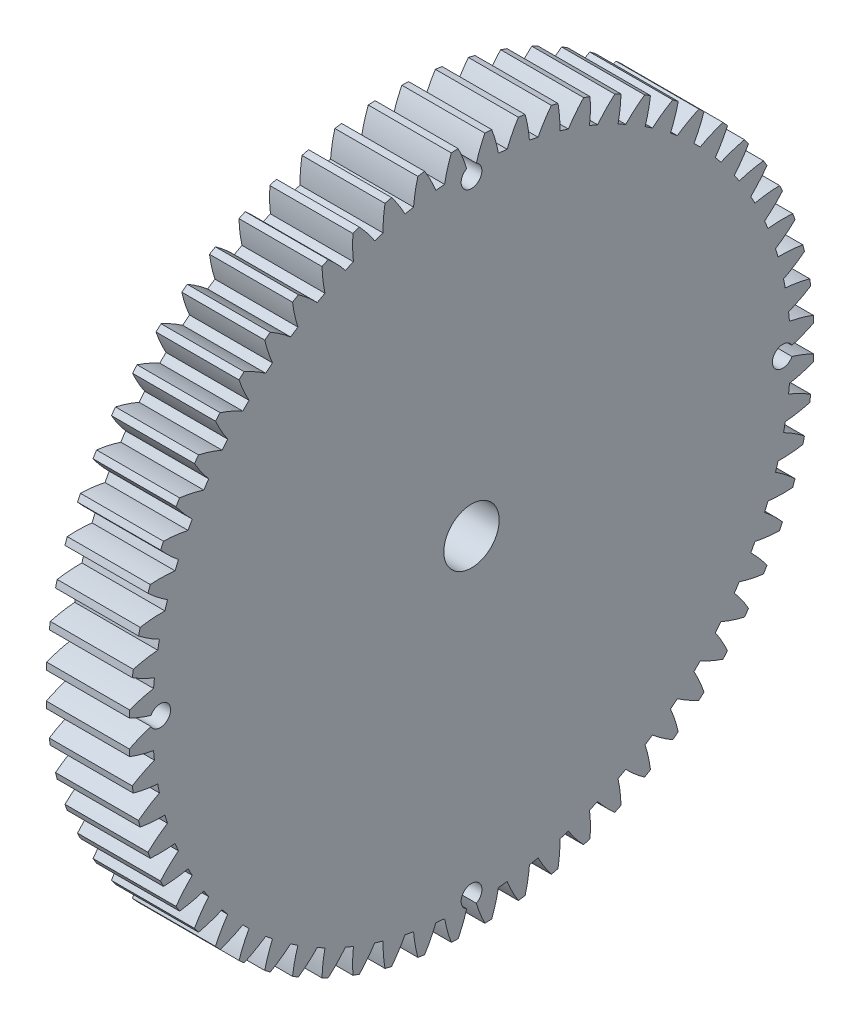
SolidWorks part; units mm, degrees
ref_plane "Plane1" through (0, 0, 0) normal (0, 0, 1) x (1, 0, 0)
ref_plane "Plane2" through (0, 0, 0) normal (0, 1, 0) x (1, 0, 0)
ref_plane "Plane3" through (0, 0, 0) normal (1, 0, 0) x (0, 0, -1)
sketch "HoldingSke" plane through (0, 0, 0) normal (0, 1, 0) x (1, 0, 0)
  line L0 (0, 0) -> (0.2922, -0.5992)
  line L1 (-15, 0) -> (100, 0) construction
  line L2 (0, 0) -> (-2.1039, 2.3779)
  line L3 (0, 0) -> (-11.863, 4.5341)
  line L4 (0, 0) -> (3.7858, 7.762)
  line L5 (0, 0) -> (-46.8476, -17.4728)
  line L6 (0, 0) -> (-9.9476, -6.7116)
  line L7 (-2.1039, 2.3779) -> (8.6586, 51.2059)
  line L8 (-76.2, 54.61) -> (-74.8, 54.61)
  line L9 (-71.009, 38.7566) -> (-53.1078, 45.2721)
  line L10 (-76.2, 71.12) -> (104.1128, 71.12)
  line L11 (0, 0) -> (-12, 0)
  line L12 (-76.2, 101.6) -> (-76.147, 101.6)
  line L13 (24.9733, 27.94) -> (52.9518, 28.4284)
  line L14 (24.9733, 27.94) -> (24.9743, 27.94)
  line L15 (24.9733, 27.94) -> (100.4006, 29.5858)
  line L16 (-63.627, -1.5) -> (-12.827, -1.5)
  circle A0 centre (0, 0) radius 4
  circle A1 centre (0, 0) radius 37.5
  circle A2 centre (0, 0) radius 37.5
  circle A3 centre (0, 0) radius 4
  dimension "MHD" = 75
  dimension "Hub_dia" = 75
  dimension "Bore" = 8
  dimension "MBD" = 8
  dimension "Num_teeth" = 64
  dimension "Pitch" = 0.6667
  dimension "Overall_len" = 50
  dimension "Show_teeth" = 64
  dimension "Thickness" = 12
  dimension "OAL" = 50.0001
  dimension "T_dim" = 1.4
  dimension "Ap" = 20
  dimension "H" = 19.05
  dimension "Pitch_radius" = 180.3128
  dimension "Width" = 12
  dimension "Backlash" = 0.053
  dimension "Addendum_fac" = 1
  dimension "Dedendum_fac" = 1.25
  dimension "Clearance_fac" = 0.25
  dimension "Dedendum_add" = 0.001
  dimension "Module" = 1.5
sketch "BasProSke" plane through (0, 0, 0) normal (0, 1, 0) x (1, 0, 0)
  line L0 (-10, 0) -> (60, 0) construction
  line L1 (0, 0) -> (0, 49.5)
  line L2 (0, 0) -> (12, 0)
  line L3 (12, 0) -> (12, 49.5)
  line L4 (12, 49.5) -> (0, 49.5)
  dimension "Thickness" = 12
  dimension "Diameter" = 99
revolve "Base-Revolve" add sketch "BasProSke" angle 360 about L0
sketch "TooCutSke" plane through (0, 0, 0) normal (1, 0, 0) x (0, 0, -1)
  line L1 (0, 0) -> (0, 107) construction
  line L2 (0, 0) -> (-1.2707, 47.9832) construction
  line L3 (0, 0) -> (-4.7093, 95.8599) construction
  line L4 (-1.2707, 47.9832) -> (-2.3546, 47.9299) construction
  arc A0 (0.6351, 46.1196) -> (-0.6351, 46.1196) centre (0, 0) ccw
  arc A1 (1.9477, 49.4871) -> (-1.9477, 49.4871) centre (0, 0) ccw
  circle A2 centre (0, 0) radius 48 construction
  circle A3 centre (0, 0) radius 45.1052 construction
  arc A4 (-0.6351, 46.1196) -> (-1.9477, 49.4871) centre (-19.101, 40.8612) ccw
  arc A5 (1.9477, 49.4871) -> (0.6351, 46.1196) centre (19.101, 40.8612) ccw
  dimension "Root_dia" = 92.248
  dimension "Overcut_dia" = 99.0508
  dimension "Pitch_dia" = 96
  dimension "Base_dia" = 90.2105
  dimension "Flank_rad" = 19.2
  dimension "Half_ang" = 2.813
  dimension "Half_CT" = 1.0852
extrude "ToothCut" cut sketch "TooCutSke" along normal through all
fillet "Breaks" [suppressed] radius 0.03
fillet "RootFillets" [suppressed] radius 0.376
pattern_circular "TeethCuts" count 64 every 5.625 about axis through (-10, 0, 0) along (1, 0, 0) of "ToothCut", "RootFillets", "Breaks"
sketch "HubNeaOneSke" plane through (0, 0, 0) normal (-1, 0, 0) x (0, 0, 1)
  circle A0 centre (0, 0) radius 37.5
  dimension "Diameter" = 75
extrude "HubNearOne" [suppressed] add sketch "HubNeaOneSke" along normal blind 38.0001
sketch "HubNeaBotSke" plane through (0, 0, 0) normal (-1, 0, 0) x (0, 0, 1)
  circle A0 centre (0, 0) radius 37.5
  dimension "Diameter" = 75
extrude "HubNearBoth" [suppressed] add sketch "HubNeaBotSke" along normal blind 19
ref_plane "FarPln" through (12, 0, 0) normal (1, 0, 0) x (0, 0, -1)
sketch "HubFarSke" plane through (12, 0, 0) normal (1, 0, 0) x (0, 0, -1)
  circle A0 centre (0, 0) radius 37.5
  dimension "Diameter" = 75
extrude "HubFar" [suppressed] add sketch "HubFarSke" along normal blind 19
sketch "BorSke" plane through (0, 0, 0) normal (1, 0, 0) x (0, 0, -1)
  circle A0 centre (0, 0) radius 4
  dimension "Diameter" = 8
extrude "Bore" cut sketch "BorSke" along normal mid plane 100.0001
sketch "KeySke" plane through (0, 0, 0) normal (1, 0, 0) x (0, 0, -1)
  line L0 (-1.5, 0) -> (-1.5, 5.4)
  line L1 (-1.5, 5.4) -> (1.5, 5.4)
  line L2 (1.5, 5.4) -> (1.5, 0)
  line L3 (0, 0) -> (0, 34) construction
  line L4 (-1.5, 0) -> (1.5, 0)
  dimension "Offset" = 5.4
  dimension "Width" = 3
extrude "Keyway" [suppressed] cut sketch "KeySke" along normal mid plane 100.0001
pattern_circular "Keyway2" [suppressed] count 2 every 90 about axis through (-10, 0, 0) along (1, 0, 0)
sketch "Sketch3" plane through (12, 0, 0) normal (1, 0, 0) x (0, 0, -1)
  line L0 (0, 0) -> (0, 45) construction
  line L1 (0, 43.7615) -> (0, 0) construction
  line L2 (0, 0) -> (70.0912, 0) construction
  line L3 (-45, 0) -> (0, 0) construction
  line L5 (0, -45) -> (0, 0) construction
  line L6 (45, 0) -> (0, 0) construction
  circle A0 centre (0, 45) radius 1.5
  circle A1 centre (45, 0) radius 1.5
  circle A2 centre (0, -45) radius 1.5
  circle A3 centre (-45, 0) radius 1.5
  dimension "D2" = 3
  dimension "D1" = 45
extrude "Cut-Extrude1" cut sketch "Sketch3" against normal through all
equation "' \"Module@HoldingSke\" = 6.35"
equation "' \"Num_teeth@HoldingSke\" = 12"
equation "' \"Ap@HoldingSke\" =  20"
equation "' \"Ap@HoldingSke\" = 20"
equation "' \"Width@HoldingSke\" = 0.5 * 25.4"
equation "' \"Hub_dia@HoldingSke\"= 1 * 25.4"
equation "' \"Hub_dia@HoldingSke\" = 1 * 25.4"
equation "' \"Overall_len@HoldingSke\" = 1.0 * 25.4"
equation "' \"Bore@HoldingSke\" = 0.75 * 25.4"
equation "' \"T_dim@HoldingSke\" = 0.1 * 25.4"
equation "' \"Width@KeySke\" = 0.25 * 25.4"
equation "' \"Show_teeth@HoldingSke\" = 13"
equation "' \"Backlash@HoldingSke\" = 0.009 * 25.4"
equation "' \"Addendum_fac@HoldingSke\" = 1.0"
equation "' \"Dedendum_fac@HoldingSke\" = 1.25"
equation "' \"Dedendum_add@HoldingSke\" = 0.00005 * 25.4"
equation "' \"Clearance_fac@HoldingSke\" = 0.25"
equation "\"Pitch@HoldingSke\" = 1 / \"Module@HoldingSke\""
equation "\"Overcut_dia@TooCutSke\" = (\"Num_teeth@HoldingSke\" + 2 * \"Addendum_fac@HoldingSke\") / \"Pitch@HoldingSke\" + 0.002 * 25.4"
equation "\"Pitch_dia@TooCutSke\" = \"Num_teeth@HoldingSke\" / \"Pitch@HoldingSke\""
equation "\"Base_dia@TooCutSke\" = \"Num_teeth@HoldingSke\" / \"Pitch@HoldingSke\" * cos((\"Ap@HoldingSke\"  * 3.14159265 / 180))"
equation "\"Root_dia@TooCutSke\" = (\"Num_teeth@HoldingSke\" + 2) / \"Pitch@HoldingSke\" - 2 * (\"Addendum_fac@HoldingSke\" + \"Dedendum_fac@HoldingSke\") / \"Pitch@HoldingSke\" - \"Dedendum_add@HoldingSke\" * 2"
equation "\"Half_ang@TooCutSke\" = 180 / \"Num_teeth@HoldingSke\""
equation "\"Half_CT@TooCutSke\" = \"Num_teeth@HoldingSke\" / \"Pitch@HoldingSke\" * sin((3.14159265 / 2 / \"Num_teeth@HoldingSke\")) / 2 - 7 * \"Backlash@HoldingSke\" / 4"
equation "\"Flank_rad@TooCutSke\" = \"Num_teeth@HoldingSke\" / \"Pitch@HoldingSke\" / 5"
equation "\"Radius@RootFillets\" = \"Clearance_fac@HoldingSke\" / \"Pitch@HoldingSke\" + \"Dedendum_add@HoldingSke\""
equation "\"Break_rad@Breaks\" = 0.02 / \"Pitch@HoldingSke\""
equation "\"Thickness@HoldingSke\" = \"Width@HoldingSke\""
equation "\"OAL@HoldingSke\" = \"Thickness@HoldingSke\""
equation "\"MHD@HoldingSke\" = (\"Num_teeth@HoldingSke\" + 2) / \"Pitch@HoldingSke\" - 2 * (\"Addendum_fac@HoldingSke\" + \"Dedendum_fac@HoldingSke\")  / \"Pitch@HoldingSke\" - \"Dedendum_add@HoldingSke\" * 2"
equation "\"MBD@HoldingSke\" = (\"Num_teeth@HoldingSke\" + 2) / \"Pitch@HoldingSke\" - 2 * (\"Addendum_fac@HoldingSke\" + \"Dedendum_fac@HoldingSke\")  / \"Pitch@HoldingSke\" - \"Dedendum_add@HoldingSke\" * 2 - 0.002 * 25.4"
equation "\"MHD@HoldingSke\" = ((sgn( \"MHD@HoldingSke\" - \"Hub_dia@HoldingSke\" )-1)*( \"MHD@HoldingSke\" - \"Hub_dia@HoldingSke\" ))/-2+ \"Hub_dia@HoldingSke\""
equation "\"MBD@HoldingSke\" = ((sgn( \"MBD@HoldingSke\" - \"Bore@HoldingSke\" )-1)*( \"MBD@HoldingSke\" - \"Bore@HoldingSke\" ))/-2+ \"Bore@HoldingSke\""
equation "\"OAL@HoldingSke\" = ((sgn( \"OAL@HoldingSke\" - \"Overall_len@HoldingSke\" )+1)*( \"OAL@HoldingSke\" - \"Overall_len@HoldingSke\" ))/2 + \"Overall_len@HoldingSke\" + 0.000002 * 25.4"
equation "\"Num_teeth@TeethCuts\" = int( \"Show_teeth@HoldingSke\" ) + 1"
equation "\"Num_teeth@TeethCuts\" = ((sgn( \"Num_teeth@TeethCuts\" - \"Num_teeth@HoldingSke\" )-1)*( \"Num_teeth@TeethCuts\" - \"Num_teeth@HoldingSke\" ))/-2+ \"Num_teeth@HoldingSke\""
equation "\"Num_teeth@TeethCuts\" = ((sgn( \"Num_teeth@TeethCuts\" - 2.0)+1)*( \"Num_teeth@TeethCuts\" - 2.0))/2 +2.0"
equation "\"Angle@TeethCuts\" = 360.0 / \"Num_teeth@HoldingSke\""
equation "\"Diameter@BasProSke\" = (\"Num_teeth@HoldingSke\" + 2 * \"Addendum_fac@HoldingSke\") / \"Pitch@HoldingSke\""
equation "\"Thickness@BasProSke\"  = \"Thickness@HoldingSke\""
equation "' \"Fillet_rad@BasProSke\" =  \"Thickness@HoldingSke\" * 0.05"
equation "' \"Fillet_rad@BasProSke\" = \"Thickness@HoldingSke\" * 0.05"
equation "\"MHD@HoldingSke\" = ((sgn( \"MHD@HoldingSke\" - \"Root_dia@TooCutSke\" )-1)*( \"MHD@HoldingSke\" - \"Root_dia@TooCutSke\" ))/-2+ \"Root_dia@TooCutSke\""
equation "\"Diameter@HubNeaOneSke\" = \"MHD@HoldingSke\""
equation "\"Length@HubNearOne\" = \"OAL@HoldingSke\" - \"Thickness@BasProSke\""
equation "\"Diameter@HubNeaBotSke\" = \"MHD@HoldingSke\""
equation "\"Length@HubNearBoth\" = ( \"OAL@HoldingSke\" - \"Thickness@BasProSke\" ) / 2.0"
equation "\"Thickness@FarPln\" = \"Thickness@BasProSke\""
equation "\"Diameter@HubFarSke\" = \"MHD@HoldingSke\""
equation "\"Length@HubFar\" = ( \"OAL@HoldingSke\" - \"Thickness@BasProSke\" ) / 2.0"
equation "\"Diameter@BorSke\" = \"MBD@HoldingSke\""
equation "\"D1@Bore\" = \"OAL@HoldingSke\" * 2.0"
equation "\"D1@Keyway\" = \"OAL@HoldingSke\" * 2.0"
equation "\"Offset@KeySke\" = \"T_dim@HoldingSke\" + \"MBD@HoldingSke\" / 2.0"
